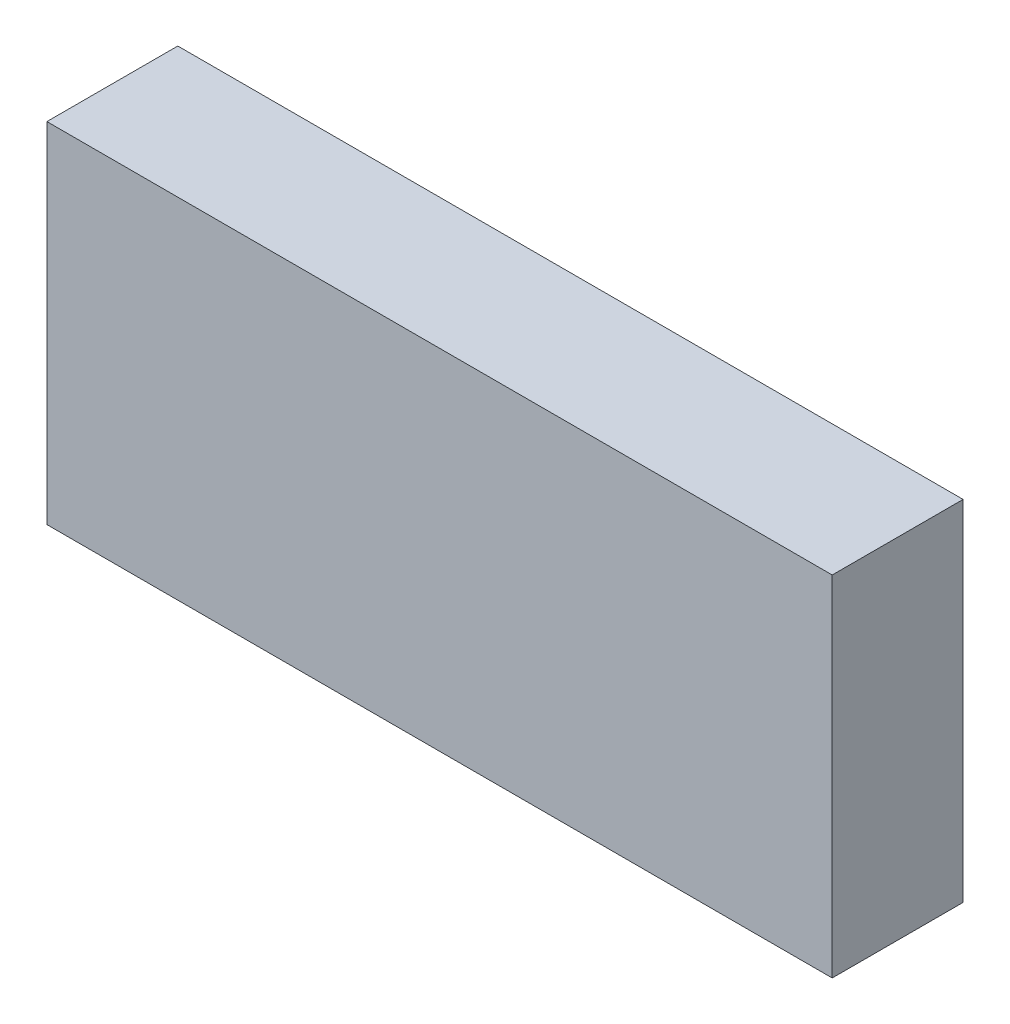
SolidWorks part; units mm, degrees
material "1060 Alloy"
ref_plane "Front Plane" through (0, 0, 0) normal (0, 0, 1) x (1, 0, 0)
ref_plane "Top Plane" through (0, 0, 0) normal (0, 1, 0) x (1, 0, 0)
ref_plane "Right Plane" through (0, 0, 0) normal (1, 0, 0) x (0, 0, -1)
sketch "Sketch1" plane through (0, 0, 0) normal (0, 0, 1) x (1, 0, 0)
  line L1 (0, 0) -> (900, 0)
  line L2 (0, 0) -> (0, 400)
  line L3 (0, 400) -> (900, 400)
  line L4 (900, 0) -> (900, 400)
  dimension "Length" = 0
  dimension "Width" = 0
extrude "Boss-Extrude1" add sketch "Sketch1" along normal blind 150
